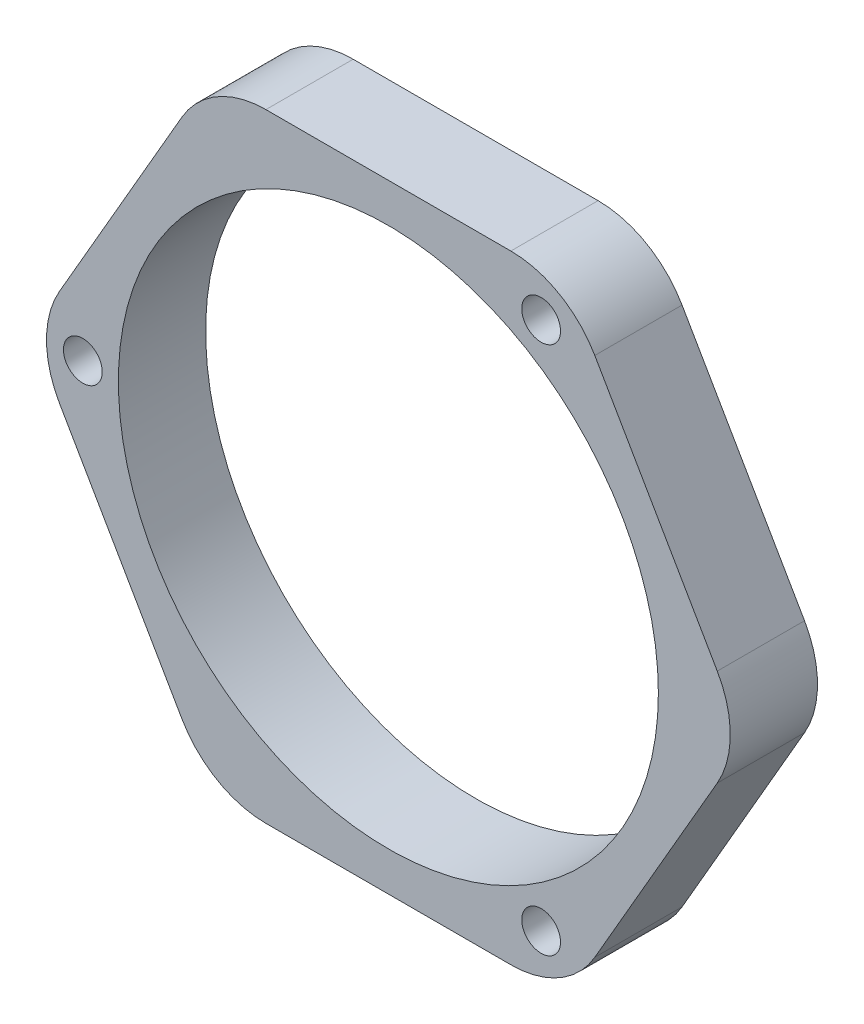
SolidWorks part; units mm, degrees
ref_plane "Front Plane" through (0, 0, 0) normal (0, 0, 1) x (1, 0, 0)
ref_plane "Top Plane" through (0, 0, 0) normal (0, 1, 0) x (1, 0, 0)
ref_plane "Right Plane" through (0, 0, 0) normal (1, 0, 0) x (0, 0, -1)
sketch "Sketch1" plane through (0, 0, 0) normal (0, 0, 1) x (1, 0, 0)
  line L1 (18.4059, -31.88) -> (36.8119, 0)
  line L2 (36.8119, 0) -> (18.4059, 31.88)
  line L3 (18.4059, 31.88) -> (-18.4059, 31.88)
  line L4 (-18.4059, 31.88) -> (-36.8119, 0)
  line L5 (-36.8119, 0) -> (-18.4059, -31.88)
  line L6 (-18.4059, -31.88) -> (18.4059, -31.88)
  circle A0 centre (0, 0) radius 27.85
  circle A1 centre (0, 0) radius 31.88 construction
  dimension "D1" = 63.76
  dimension "D2" = 55.7
extrude "Boss-Extrude1" add sketch "Sketch1" along normal blind 9
fillet "Fillet1" radius 10 6 edges at (-18.4059, -31.88, 4.5) (18.4059, -31.88, 4.5) (-36.8119, 0, 4.5) (36.8119, 0, 4.5) (18.4059, 31.88, 4.5) (-18.4059, 31.88, 4.5)
sketch "Sketch3" plane through (0, 0, 9) normal (0, 0, 1) x (1, 0, 0)
  line L0 (0, 0) -> (-35.2648, 0) construction
  arc A0 (-33.9251, 5) -> (-33.9251, -5) centre (-25.2648, 0) ccw construction
  circle A1 centre (-31.5148, 0) radius 3.75 construction
  circle A2 centre (-31.5148, 0) radius 2
  dimension "D1" = 7.5
  dimension "D2" = 4
extrude "Cut-Extrude1" cut sketch "Sketch3" against normal through all contours A2
pattern_circular "CirPattern1" count 3 over 360 about axis through (0, 0, 0) along (0, 0, 1) of "Cut-Extrude1"
equation "\"Depth\"= 9mm"
equation "\"de\"=5"
equation "\"D1@Boss-Extrude1\"=\"Depth\""
